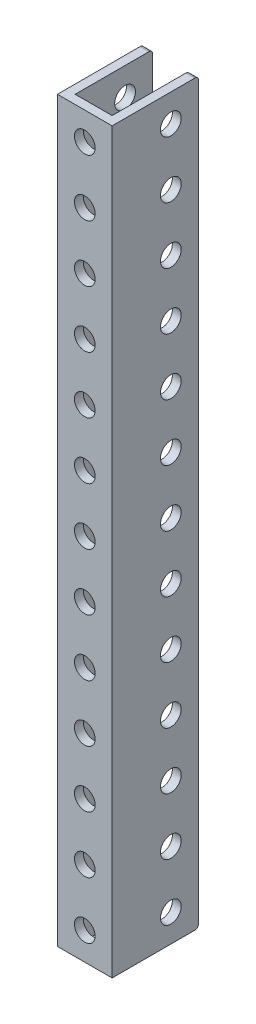
SolidWorks part; units mm, degrees
ref_plane "Front Plane" through (0, 0, 0) normal (0, 0, 1) x (1, 0, 0)
ref_plane "Top Plane" through (0, 0, 0) normal (0, 1, 0) x (1, 0, 0)
ref_plane "Right Plane" through (0, 0, 0) normal (1, 0, 0) x (0, 0, -1)
ref_plane "Plane1" through (-4.699, 0, 0) normal (-1, 0, 0) x (0, -1, 0)
sketch "Sketch1" plane through (-4.699, 0, 0) normal (-1, 0, 0) x (0, -1, 0)
  line L0 (-126.873, -13.335) -> (0, -13.335)
  line L1 (0, -13.335) -> (0, 1.524)
  line L2 (0, 1.524) -> (-126.873, 1.524)
  line L3 (-126.873, 1.524) -> (-126.873, -13.335)
extrude "Boss-Extrude1" add sketch "Sketch1" against normal blind 9.398
sketch "Sketch2" plane through (0, 0, 0) normal (0, -1, 0) x (1, 0, 0)
  line L0 (-3.175, -13.335) -> (3.175, -13.335)
  line L1 (3.175, -13.335) -> (3.175, 0)
  line L2 (3.175, 0) -> (-3.175, 0)
  line L3 (-3.175, 0) -> (-3.175, -13.335)
extrude "Cut-Extrude1" cut sketch "Sketch2" against normal through all
hole_wizard "#5 Clearance Hole1" positions "Sketch4" profile "Sketch3" hole size "#5" standard "ANSI Inch"
sketch "Sketch4" plane through (4.699, 0, 0) normal (1, 0, 0) x (0, 0, -1)
  point P0 (8.5725, 112.3315)
  point P1 (8.5725, 122.1105)
  point P2 (8.5725, 102.5525)
  point P3 (8.5725, 92.7735)
  point P4 (8.5725, 82.9945)
  point P5 (8.5725, 73.2155)
  point P6 (8.5725, 63.4365)
  point P7 (8.5725, 53.6575)
  point P8 (8.5725, 43.8785)
  point P9 (8.5725, 34.0995)
  point P10 (8.5725, 24.3205)
  point P11 (8.5725, 14.5415)
  point P12 (8.5725, 4.7625)
sketch "Sketch3" plane through (4.699, 112.3315, -8.5725) normal (0, 1, 0) x (0, 0, -1)
  line L0 (0, 0) -> (0, 1.524)
  line L1 (0, 1.524) -> (1.778, 1.524)
  line L2 (1.778, 1.524) -> (1.778, 0)
  line L5 (1.778, 0) -> (0, 0)
  line L11 (0, -6.35) -> (0, 107.95) construction
  dimension "Thru Hole Dia." = 3.556
  dimension "Thru Hole Depth" = 1.524
hole_wizard "#5 Clearance Hole2" positions "Sketch6" profile "Sketch5" hole size "#5" standard "ANSI Inch"
sketch "Sketch6" plane through (0, 0, 1.524) normal (0, 0, 1) x (1, 0, 0)
  point P0 (0, 112.3315)
  point P1 (0, 122.1105)
  point P2 (0, 102.5525)
  point P3 (0, 92.7735)
  point P4 (0, 82.9945)
  point P5 (0, 73.2155)
  point P6 (0, 63.4365)
  point P7 (0, 53.6575)
  point P8 (0, 43.8785)
  point P9 (0, 34.0995)
  point P10 (0, 24.3205)
  point P11 (0, 14.5415)
  point P12 (0, 4.7625)
sketch "Sketch5" plane through (0, 112.3315, 1.524) normal (1, 0, 0) x (0, -1, 0)
  line L0 (0, 0) -> (0, 14.859)
  line L1 (0, 14.859) -> (1.778, 14.859)
  line L2 (1.778, 14.859) -> (1.778, 0)
  line L5 (1.778, 0) -> (0, 0)
  line L11 (0, -6.35) -> (0, 107.95) construction
  dimension "Thru Hole Dia." = 3.556
  dimension "Thru Hole Depth" = 14.859
hole_wizard "#5 Clearance Hole3" positions "Sketch8" profile "Sketch7" hole size "#5" standard "ANSI Inch"
sketch "Sketch8" plane through (-3.175, 0, 0) normal (1, 0, 0) x (0, 0, -1)
  point P0 (8.5725, 112.3315)
  point P1 (8.5725, 122.1105)
  point P2 (8.5725, 102.5525)
  point P3 (8.5725, 92.7735)
  point P4 (8.5725, 82.9945)
  point P5 (8.5725, 73.2155)
  point P6 (8.5725, 63.4365)
  point P7 (8.5725, 53.6575)
  point P8 (8.5725, 43.8785)
  point P9 (8.5725, 34.0995)
  point P10 (8.5725, 24.3205)
  point P11 (8.5725, 14.5415)
  point P12 (8.5725, 4.7625)
sketch "Sketch7" plane through (-3.175, 112.3315, -8.5725) normal (0, 1, 0) x (0, 0, -1)
  line L0 (0, 0) -> (0, 1.524)
  line L1 (0, 1.524) -> (1.778, 1.524)
  line L2 (1.778, 1.524) -> (1.778, 0)
  line L5 (1.778, 0) -> (0, 0)
  line L11 (0, -6.35) -> (0, 107.95) construction
  dimension "Thru Hole Dia." = 3.556
  dimension "Thru Hole Depth" = 1.524
fillet "Fillet1" radius 0.635 4 edges at (3.937, 0, -13.335) (3.937, 126.873, -13.335) (-3.937, 126.873, -13.335) (-3.937, 0, -13.335)
